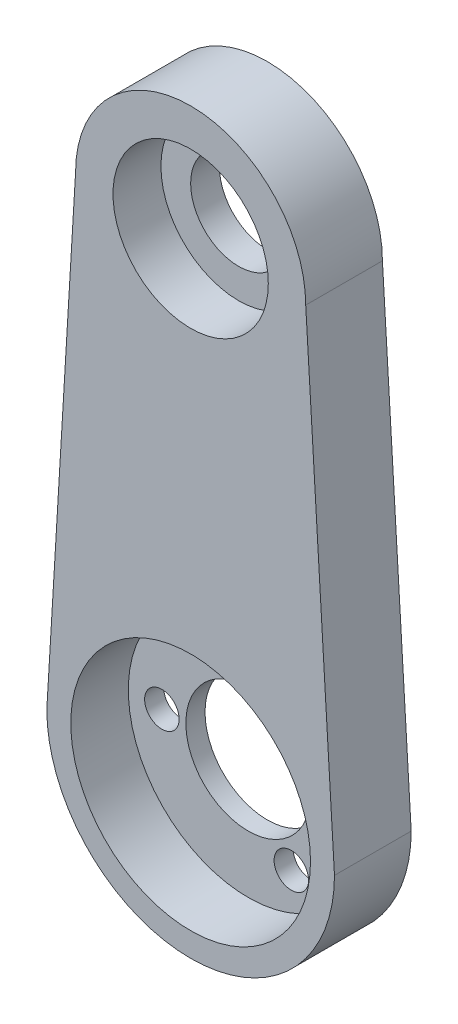
SolidWorks part; units mm, degrees
ref_plane "Plan de face" through (0, 0, 0) normal (0, 0, 1) x (1, 0, 0)
ref_plane "Plan de dessus" through (0, 0, 0) normal (0, 1, 0) x (1, 0, 0)
ref_plane "Plan de droite" through (0, 0, 0) normal (1, 0, 0) x (0, 0, -1)
sketch "Esquisse1" plane through (0, 0, 0) normal (0, 0, 1) x (1, 0, 0)
  line L0 (-16.3093, 0) -> (24.5372, 0) construction
  line L1 (12, 0) -> (15, -50)
  line L2 (-12, 0) -> (-15, -50)
  line L3 (-15, -50) -> (15, -50) construction
  line L4 (0, 0) -> (0, -50) construction
  arc A0 (-12, 0) -> (12, 0) centre (0, 0) cw
  arc A1 (-15, -50) -> (15, -50) centre (0, -50) ccw
  dimension "D1" = 12
  dimension "D2" = 15
  dimension "D3" = 50
extrude "Boss.-Extru.1" add sketch "Esquisse1" along normal blind 8
sketch "Esquisse2" plane through (0, 0, 8) normal (0, 0, 1) x (1, 0, 0)
  line L0 (0, 0) -> (0, -65) construction
  line L1 (15, -50) -> (-15, -50) construction
  circle A0 centre (0, -50) radius 6.5
  arc A1 (-15, -50) -> (15, -50) centre (0, -50) ccw construction
extrude "Enlèv. mat.-Extru.1" cut sketch "Esquisse2" against normal blind 10
sketch "Esquisse3" plane through (0, 0, 8) normal (0, 0, 1) x (1, 0, 0)
  line L0 (0, -50) -> (0, 0) construction
  line L1 (0, -50) -> (4.5, -42.2058) construction
  line L4 (0, -50) -> (-9, -50) construction
  line L5 (-9, -50) -> (0, -50) construction
  line L6 (0, -50) -> (4.5, -57.7942) construction
  circle A6 centre (4.5, -57.7942) radius 1.8
  circle A7 centre (-9, -50) radius 1.8
  circle A8 centre (4.5, -42.2058) radius 1.8
  dimension "D1" = 120
  dimension "D2" = 120
  dimension "D3" = 9
extrude "Enlèv. mat.-Extru.2" cut sketch "Esquisse3" against normal blind 10
ref_plane "Plan1" through (0, 10, 0) normal (0, 1, 0) x (1, 0, 0)
sketch "Esquisse5" plane through (0, 0, 8) normal (0, 0, 1) x (1, 0, 0)
  circle A0 centre (0, -50) radius 12.5
  dimension "D1" = 25
extrude "Enlèv. mat.-Extru.5" cut sketch "Esquisse5" against normal blind 6
sketch "Esquisse19" plane through (0, 0, 8) normal (0, 0, 1) x (1, 0, 0)
  circle A0 centre (0, 0) radius 8.1
extrude "Enlèv. mat.-Extru.6" cut sketch "Esquisse19" against normal blind 10 contours A0
sketch "Esquisse21" plane through (0, 0, 0) normal (0, 0, -1) x (-1, 0, 0)
  line L0 (-12, 0) -> (-15, -50)
  line L1 (12, 0) -> (15, -50)
  circle A0 centre (0, 0) radius 12
  circle A1 centre (0, -50) radius 15
sketch "Esquisse22" plane through (0, 0, 0) normal (0, 0, -1) x (-1, 0, 0)
  circle A0 centre (0, 0) radius 8.1
  circle A1 centre (0, 0) radius 5
extrude "Boss.-Extru.2" add sketch "Esquisse22" against normal blind 3
